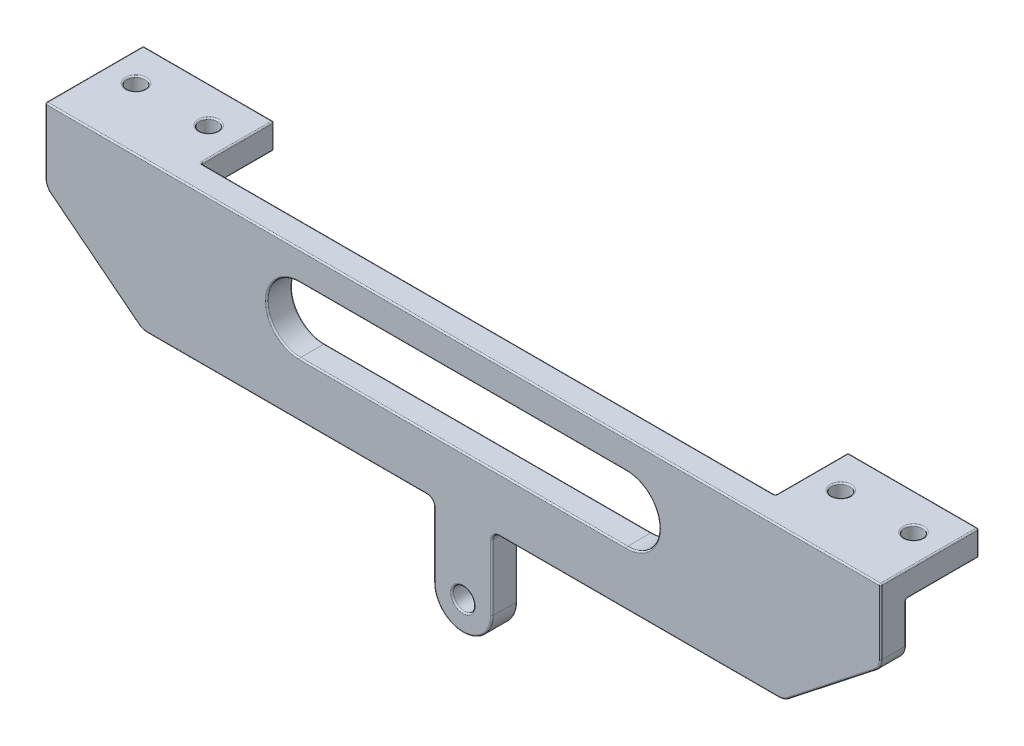
SolidWorks part; units mm, degrees
ref_plane "Front Plane" through (0, 0, 0) normal (0, 0, 1) x (1, 0, 0)
ref_plane "Top Plane" through (0, 0, 0) normal (0, 1, 0) x (1, 0, 0)
ref_plane "Right Plane" through (0, 0, 0) normal (1, 0, 0) x (0, 0, -1)
sketch "Sketch1" plane through (0, 0, 0) normal (0, 0, 1) x (1, 0, 0)
  line L0 (-100, 0) -> (100, 0) construction
  line L1 (-100, 0) -> (0, 100) construction
  line L2 (0, 100) -> (100, 0) construction
  line L3 (0, 0) -> (-50, 50) construction
  line L4 (-40, 60) -> (40, 60) construction
  line L5 (0, 100) -> (0, 60) construction
  circle A0 centre (-100, 0) radius 20
  circle A1 centre (0, 0) radius 20
  circle A2 centre (100, 0) radius 20
  point P3 (0, 0)
  dimension "D5" = 40
  dimension "D1" = 200
  dimension "D2" = 90
  dimension "D3" = 80
  dimension "D4" = 90
sketch "Sketch2" plane through (0, 0, 0) normal (0, 0, 1) x (1, 0, 0)
  line L0 (-56.5165, 43.4835) -> (-40, 60) construction
  line L1 (-100, 0) -> (0, 100) construction
  line L2 (-40, 60) -> (40, 60) construction
  line L3 (40, 60) -> (86.565, 13.435) construction
  line L4 (0, 100) -> (100, 0) construction
  line L5 (-49.4454, 36.4124) -> (-35.8579, 50)
  line L6 (-35.8579, 50) -> (35.8579, 50)
  line L7 (35.8579, 50) -> (79.4939, 6.364)
  line L8 (-63.5876, 50.5546) -> (-44.1421, 70)
  line L9 (-44.1421, 70) -> (44.1421, 70)
  line L10 (44.1421, 70) -> (93.636, 20.5061)
  line L11 (-63.5876, 50.5546) -> (-49.4454, 36.4124)
  line L12 (79.4939, 6.364) -> (93.636, 20.5061)
  line L13 (81.9812, 8.8513) -> (95.0783, -4.2458)
  line L14 (91.1473, 18.0173) -> (104.225, 4.9396)
  line L15 (75.9584, 9.8995) -> (90.1005, 24.0416) construction
  line L16 (0, 100) -> (0, 60) construction
  line L17 (-6, 70) -> (-3.5, 82)
  line L18 (6, 70) -> (3.5, 82)
  circle A0 centre (100, 0) radius 10 construction
  circle A1 centre (100, 0) radius 3.5
  arc A2 (95.0783, -4.2458) -> (104.225, 4.9396) centre (100, 0) ccw
  circle A3 centre (100, 0) radius 0.5
  circle A4 centre (79.4939, 13.435) radius 1
  circle A5 centre (100, 0) radius 6.5 construction
  circle A6 centre (86.565, 20.5061) radius 1
  circle A7 centre (0, 60) radius 1.5
  circle A8 centre (0, 82) radius 1.5
  arc A11 (3.5, 82) -> (-3.5, 82) centre (0, 82) ccw
  circle A12 centre (-50, 50) radius 1.5
  circle A13 centre (0, 82) radius 3.5 construction
  point P30 (106.5, 0)
  point P50 (3.5, 82)
  dimension "D4" = 7
  dimension "D7" = 20
  dimension "D10" = 2
  dimension "D11" = 5
  dimension "D12" = 5
  dimension "D13" = 3
  dimension "D14" = 12
  dimension "D18" = 3
  dimension "D3" = 27.5
  dimension "D8" = 19
  dimension "D9" = 5
  dimension "D16" = 6
  dimension "D17" = 6
  dimension "D1" = 10
  dimension "D2" = 10
  dimension "D5" = 3
  dimension "D6" = 3
  dimension "D15" = 2
sketch "Sketch3" plane through (0, 0, 0) normal (0, 0, 1) x (1, 0, 0)
  line L0 (-86.565, 13.435) -> (-50, 50) construction
  line L1 (-100, 0) -> (0, 100) construction
  line L2 (-50, 50) -> (-13.435, 13.435) construction
  line L3 (0, 0) -> (-50, 50) construction
  line L4 (-79.4939, 6.364) -> (-50, 35.8579)
  line L5 (-50, 35.8579) -> (-20.5061, 6.364)
  line L6 (-93.636, 20.5061) -> (-50, 64.1421)
  line L7 (-50, 64.1421) -> (-6.364, 20.5061)
  line L8 (-94.9578, 19.1843) -> (-50, 64.1421) construction
  line L9 (-80.8157, 5.0422) -> (-50, 35.8579) construction
  line L10 (-93.636, 20.5061) -> (-79.4939, 6.364)
  line L11 (-20.5061, 6.364) -> (-6.364, 20.5061)
  line L12 (-87.8868, 12.1132) -> (-50, 50) construction
  line L13 (-91.121, 17.991) -> (-103.9494, 5.1626)
  line L14 (-81.9688, 8.8389) -> (-95.425, -4.6173)
  line L15 (-17.8509, 9.0191) -> (-4.6576, -4.534)
  line L16 (-8.8388, 18.0312) -> (4.5962, 4.5962)
  line L17 (-90.1005, 24.0416) -> (-75.9584, 9.8995) construction
  line L18 (-24.0416, 9.8995) -> (-9.8995, 24.0416) construction
  circle A0 centre (-100, 0) radius 10 construction
  circle A1 centre (-100, 0) radius 3.5
  circle A2 centre (0, 0) radius 10 construction
  circle A3 centre (0, 0) radius 3.5
  arc A4 (-4.6576, -4.534) -> (4.5962, 4.5962) centre (0, 0) ccw
  circle A5 centre (-100, 0) radius 6.5
  circle A6 centre (0, 0) radius 20 construction
  circle A7 centre (-86.565, 20.5061) radius 1
  circle A8 centre (0, 0) radius 6.5 construction
  circle A9 centre (-79.4939, 13.435) radius 1
  circle A10 centre (-20.5061, 13.435) radius 1
  circle A11 centre (-13.435, 20.5061) radius 1
  point P39 (6.5, 0)
  dimension "D1" = 20
  dimension "D2" = 7
  dimension "D8" = 2
  dimension "D6" = 19
  dimension "D7" = 19
  dimension "D9" = 5
  dimension "D10" = 5
  dimension "D11" = 5
  dimension "D12" = 5
  dimension "D13" = 5
  dimension "D14" = 5
  dimension "D3" = 3
  dimension "D4" = 10
  dimension "D5" = 10
sketch "Sketch4" plane through (0, 0, 0) normal (0, 0, 1) x (1, 0, 0)
  line L1 (57.5, 90.5) -> (57.5, 80.5)
  line L2 (57.5, 80.5) -> (44.1421, 70)
  line L3 (44.1421, 70) -> (-44.1421, 70)
  line L4 (-44.1421, 70) -> (-57.5, 80.5)
  line L5 (-57.5, 80.5) -> (-57.5, 90.5)
  line L6 (-57.5, 90.5) -> (57.5, 90.5)
  line L7 (-4, 60) -> (-4, 70)
  line L8 (4, 60) -> (4, 70)
  line L9 (-22.5, 82) -> (22.5, 82) construction
  line L10 (-22.5, 86.5) -> (22.5, 86.5)
  line L11 (-22.5, 77.5) -> (22.5, 77.5)
  circle A0 centre (0, 60) radius 1.5 construction
  circle A1 centre (0, 60) radius 1.5
  arc A2 (-4, 60) -> (4, 60) centre (0, 60) ccw
  arc A3 (-22.5, 86.5) -> (-22.5, 77.5) centre (-22.5, 82) ccw
  circle A4 centre (0, 60) radius 4 construction
  arc A5 (22.5, 77.5) -> (22.5, 86.5) centre (22.5, 82) ccw
  point P3 (0, 111.8578)
  point P19 (4, 60)
  point P22 (0, 82)
  dimension "D5" = 9
  dimension "D1" = 115
  dimension "D2" = 10
  dimension "D4" = 45
  dimension "D6" = 4
  dimension "D3" = 2.5
sketch "Sketch5" plane through (0, 0, 0) normal (0, 0, 1) x (1, 0, 0)
  line L0 (4, 60) -> (4, 70) construction
  line L1 (-4, 60) -> (-4, 70) construction
  line L2 (22.5, 86.5) -> (-22.5, 86.5)
  line L3 (-22.5, 77.5) -> (22.5, 77.5)
  line L4 (22.5, 86.5) -> (-22.5, 86.5)
  line L5 (-22.5, 77.5) -> (22.5, 77.5)
  line L6 (57.5, 80.5) -> (57.5, 90.5)
  line L7 (44.1421, 70) -> (57.5, 80.5)
  line L8 (-44.1421, 70) -> (44.1421, 70)
  line L9 (-57.5, 80.5) -> (-44.1421, 70)
  line L10 (-57.5, 90.5) -> (-57.5, 80.5)
  line L11 (57.5, 90.5) -> (-57.5, 90.5)
  line L12 (57.5, 80.5) -> (57.5, 90.5)
  line L13 (44.1421, 70) -> (57.5, 80.5)
  line L14 (-44.1421, 70) -> (-4, 70)
  line L15 (-57.5, 80.5) -> (-44.1421, 70)
  line L16 (-57.5, 90.5) -> (-57.5, 80.5)
  line L17 (57.5, 90.5) -> (-57.5, 90.5)
  line L18 (4, 60) -> (4, 70)
  line L19 (-4, 60) -> (-4, 70)
  line L20 (4, 70) -> (44.1421, 70)
  arc A0 (-4, 60) -> (4, 60) centre (0, 60) ccw construction
  circle A1 centre (0, 60) radius 1.5
  circle A2 centre (0, 60) radius 1.5
  arc A3 (-4, 60) -> (4, 60) centre (0, 60) ccw
  arc A4 (22.5, 77.5) -> (22.5, 86.5) centre (22.5, 82) ccw
  arc A5 (-22.5, 86.5) -> (-22.5, 77.5) centre (-22.5, 82) ccw
  arc A6 (22.5, 77.5) -> (22.5, 86.5) centre (22.5, 82) ccw
  arc A7 (-22.5, 86.5) -> (-22.5, 77.5) centre (-22.5, 82) ccw
  dimension "D1" = 0
  dimension "D2" = 0
  dimension "D3" = 0
extrude "Boss-Extrude2" add sketch "Sketch5" along normal blind 3.5
sketch "Sketch6" plane through (0, 90.5, 0) normal (0, 1, 0) x (1, 0, 0)
  line L0 (-57.5, 0) -> (-39.5, 0)
  line L1 (57.5, 0) -> (-57.5, 0) construction
  line L2 (-39.5, 0) -> (-39.5, 10)
  line L3 (-57.5, 0) -> (-57.5, 10)
  line L4 (-57.5, 10) -> (-39.5, 10)
  line L5 (-57.5, 5) -> (-39.5, 5) construction
  line L6 (-48.5, 5) -> (-48.5, 10) construction
  line L7 (0, 0) -> (0, 27.4996) construction
  line L8 (48.5, 5) -> (48.5, 10) construction
  line L9 (57.5, 5) -> (39.5, 5) construction
  line L10 (57.5, 10) -> (39.5, 10)
  line L11 (57.5, 0) -> (57.5, 10)
  line L12 (39.5, 0) -> (39.5, 10)
  line L13 (57.5, 0) -> (39.5, 0)
  circle A0 centre (-53.5, 5) radius 1.25
  circle A1 centre (-43.5, 5) radius 1.25
  circle A2 centre (43.5, 5) radius 1.25
  circle A3 centre (53.5, 5) radius 1.25
  dimension "D3" = 2.5
  dimension "D5" = 4
  dimension "D1" = 10
  dimension "D2" = 18
  dimension "D4" = 10
  dimension "D6" = 5
  dimension "D7" = 5
extrude "Boss-Extrude3" add sketch "Sketch6" against normal blind 3.5
fillet "Fillet1" radius 2 4 edges at (-44.1421, 70, 1.75) (-57.5, 80.5, 1.75) (57.5, 80.5, 1.75) (44.1421, 70, 1.75)
fillet "Fillet2" radius 1 2 edges at (-4, 70, 1.75) (4, 70, 1.75)
fillet "Fillet3" radius 0.2 70 edges at (39.5, 88.75, 0) (39.5, 88.75, -10) (57.5, 88.75, -10) (48.5, 87, 0) (39.5, 87, -5) (48.5, 87, -10) (57.5, 87, -5) (39.5, 90.5, -5) (48.5, 90.5, -10) (43.5, 87, -6.25) (43.5, 90.5, -6.25) (53.5, 87, -6.25) (53.5, 90.5, -6.25) (-43.5, 90.5, -3.75) (-43.5, 87, -3.75) (-53.5, 90.5, -3.75) (-53.5, 87, -3.75) (-39.5, 90.5, -5) (-39.5, 87, -5) (-48.5, 90.5, -10) (-48.5, 87, -10) (-57.5, 87, -5) (-48.5, 87, 0) (-39.5, 88.75, 0) (-39.5, 88.75, -10) (-57.5, 88.75, -10) (0, 77.5, 0) (27, 82, 0) (0, 86.5, 0) (-27, 82, 3.5) (0, 77.5, 3.5) (27, 82, 3.5) (0, 86.5, 3.5) (1.5, 60, 0) (1.5, 60, 3.5) (0, 90.5, 0) (-57.5, 84.2359, 0) (-50.7111, 75.1635, 0) (-24.2251, 70, 0) (-4, 64.5, 0) (0, 56, 0) (4, 64.5, 0) (24.2251, 70, 0) (50.7111, 75.1635, 0) (57.5, 84.2359, 0) (0, 90.5, 3.5) (-57.5, 85.9859, 3.5) (-50.7111, 75.1635, 3.5) (-24.2251, 70, 3.5) (-4, 64.5, 3.5) (0, 56, 3.5) (4, 64.5, 3.5) (24.2251, 70, 3.5) (50.7111, 75.1635, 3.5) (57.5, 85.9859, 3.5) (57.5, 90.5, -3.25) (-57.5, 90.5, -3.25) (44.1041, 70.1099, 0) (57.2989, 80.5977, 0) (-57.2989, 80.5977, 0) (-44.1041, 70.1099, 0) (44.1041, 70.1099, 3.5) (57.2989, 80.5977, 3.5) (-57.2989, 80.5977, 3.5) (-44.1041, 70.1099, 3.5) (-4.2929, 69.7071, 0) (-4.2929, 69.7071, 3.5) (4.2929, 69.7071, 0) (4.2929, 69.7071, 3.5) (-27, 82, 0)
